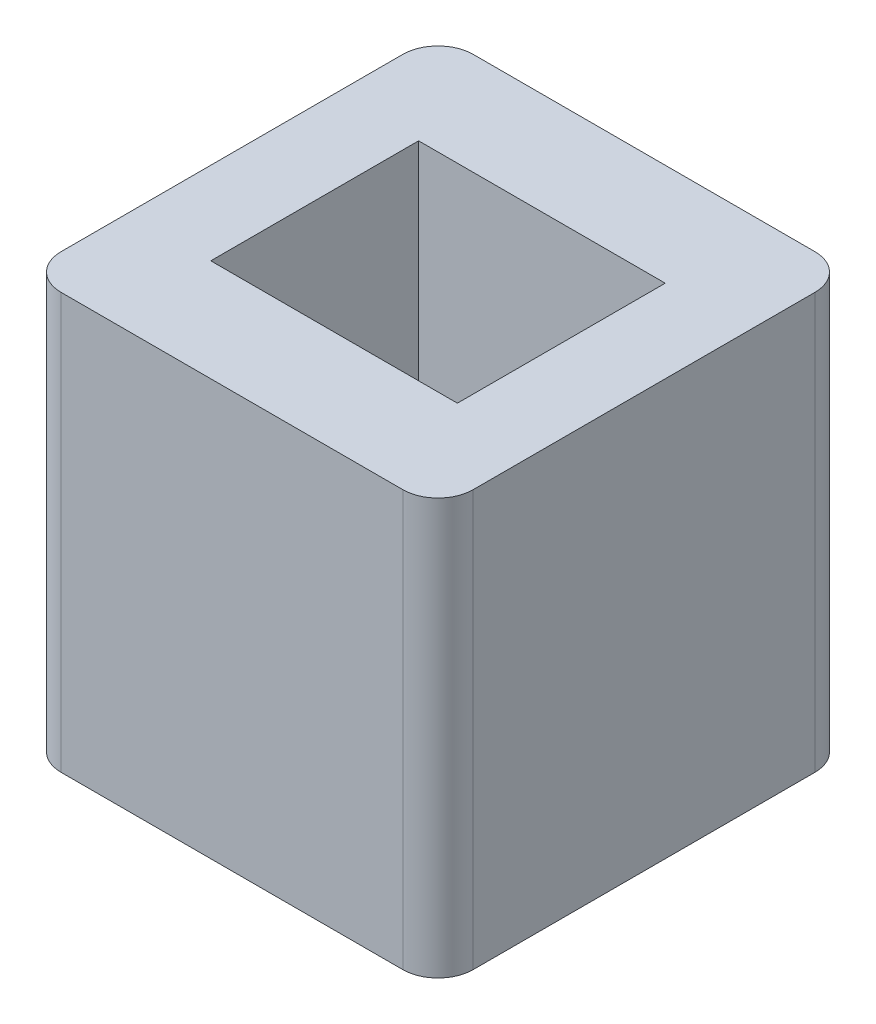
SolidWorks part; units mm, degrees
material "Copper"
ref_plane "Front Plane" through (0, 0, 0) normal (0, 0, 1) x (1, 0, 0)
ref_plane "Top Plane" through (0, 0, 0) normal (0, 1, 0) x (1, 0, 0)
ref_plane "Right Plane" through (0, 0, 0) normal (1, 0, 0) x (0, 0, -1)
sketch "Sketch1" plane through (0, 0, 0) normal (0, 1, 0) x (1, 0, 0)
  line L1 (-17.5, 14.75) -> (17.5, 14.75)
  line L2 (-17.5, 14.75) -> (-17.5, -14.75)
  line L3 (-17.5, -14.75) -> (17.5, -14.75)
  line L4 (17.5, 14.75) -> (17.5, -14.75)
  line L5 (-17.5, 14.75) -> (17.5, -14.75) construction
  line L6 (-17.5, -14.75) -> (17.5, 14.75) construction
  line L7 (-24.25, 29.25) -> (24.25, 29.25)
  line L8 (-29.25, 24.25) -> (-29.25, -24.25)
  line L9 (-24.25, -29.25) -> (24.25, -29.25)
  line L10 (29.25, 24.25) -> (29.25, -24.25)
  line L11 (-29.25, 29.25) -> (29.25, -29.25) construction
  line L12 (-29.25, -29.25) -> (29.25, 29.25) construction
  arc A0 (-24.25, -29.25) -> (-29.25, -24.25) centre (-24.25, -24.25) cw
  arc A1 (29.25, -24.25) -> (24.25, -29.25) centre (24.25, -24.25) cw
  arc A2 (29.25, 24.25) -> (24.25, 29.25) centre (24.25, 24.25) ccw
  arc A3 (-29.25, 24.25) -> (-24.25, 29.25) centre (-24.25, 24.25) cw
  point P0 (0, 0)
  point P5 (0, 0)
  dimension "D4" = 5
  dimension "D1" = 29.5
  dimension "D2" = 35
  dimension "D3" = 58.5
extrude "Boss-Extrude1" add sketch "Sketch1" along normal mid plane 59
